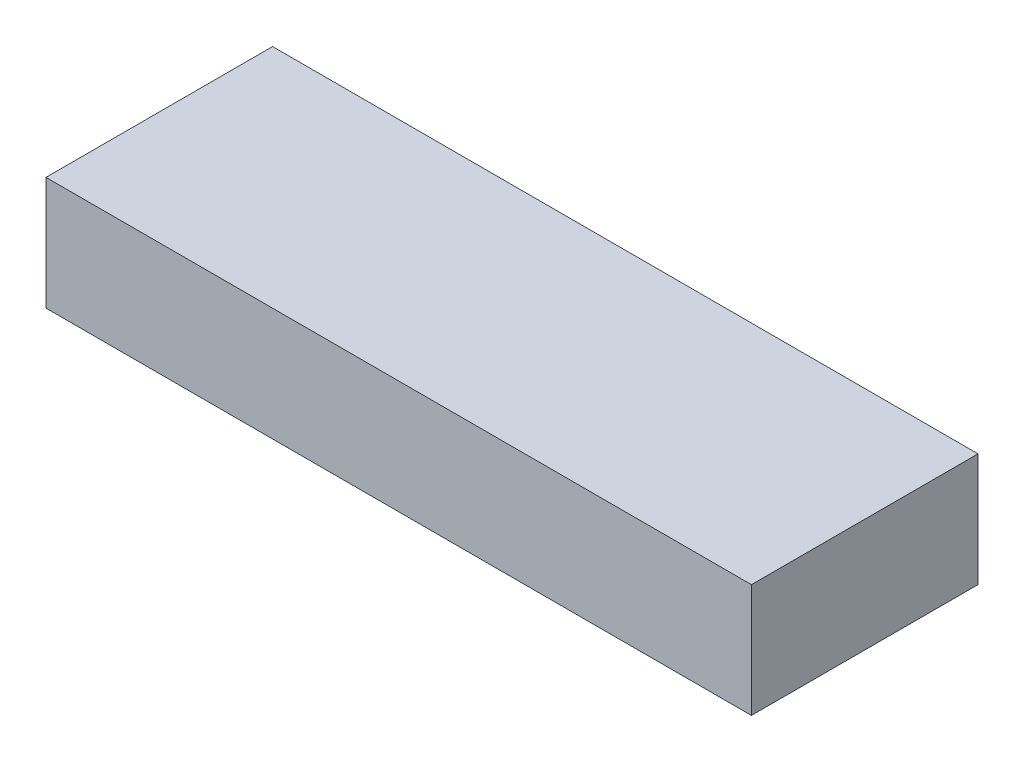
SolidWorks part; units mm, degrees
material "Plastiche personalizzate"
ref_plane "Piano frontale" through (0, 0, 0) normal (0, 0, 1) x (1, 0, 0)
ref_plane "Piano superiore" through (0, 0, 0) normal (0, 1, 0) x (1, 0, 0)
ref_plane "Piano destro" through (0, 0, 0) normal (1, 0, 0) x (0, 0, -1)
sketch "Schizzo1" plane through (0, 0, 0) normal (0, 1, 0) x (1, 0, 0)
  line L1 (-59.6912, 26.5435) -> (77.3088, 26.5435)
  line L2 (-59.6912, 26.5435) -> (-59.6912, -17.4565)
  line L3 (-59.6912, -17.4565) -> (77.3088, -17.4565)
  line L4 (77.3088, 26.5435) -> (77.3088, -17.4565)
  dimension "D1" = 137
  dimension "D2" = 44
extrude "Estrusione-Estrusione1" add sketch "Schizzo1" along normal blind 22
